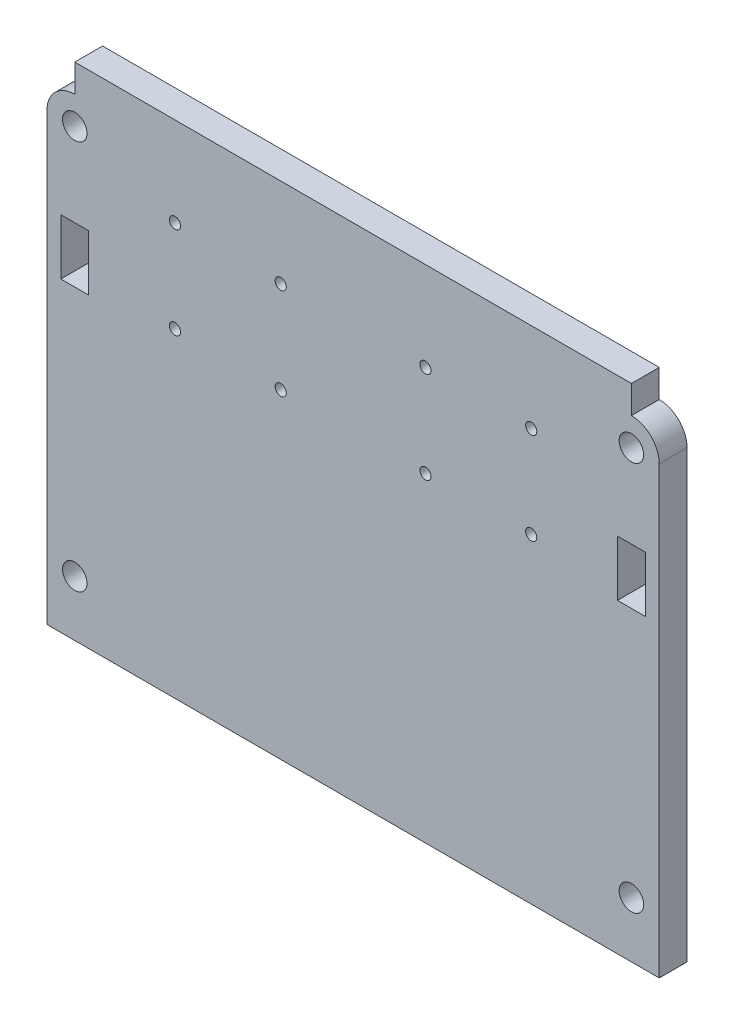
SolidWorks part; units mm, degrees
ref_plane "Front Plane" through (0, 0, 0) normal (0, 0, 1) x (1, 0, 0)
ref_plane "Top Plane" through (0, 0, 0) normal (0, 1, 0) x (1, 0, 0)
ref_plane "Right Plane" through (0, 0, 0) normal (1, 0, 0) x (0, 0, -1)
sketch "Sketch1" plane through (0, 0, 0) normal (0, 0, 1) x (1, 0, 0)
  line L0 (0, 105) -> (0, 110)
  line L1 (0, 0) -> (30.7314, 0) construction
  line L2 (0, 20) -> (0, 25) construction
  line L3 (0, 110) -> (100, 110)
  line L4 (50, 20) -> (50, 110) construction
  line L5 (0, 85) -> (2.5, 85)
  line L6 (0, 35) -> (0, 75) construction
  line L7 (0, 75) -> (2.5, 75)
  line L8 (2.5, 85) -> (2.5, 75)
  line L9 (0, 85) -> (0, 95) construction
  line L10 (0, 20) -> (100, 20)
  line L11 (0, 0) -> (0, 20) construction
  line L12 (-5, 100) -> (-5, 20)
  line L13 (0, 20) -> (-5, 20)
  line L14 (0, 85) -> (-2.5, 85)
  line L15 (-2.5, 85) -> (-2.5, 75)
  line L16 (-2.5, 75) -> (0, 75)
  line L17 (100, 85) -> (100, 95) construction
  line L18 (100, 35) -> (100, 75) construction
  line L19 (100, 20) -> (100, 25) construction
  line L20 (102.5, 75) -> (100, 75)
  line L21 (102.5, 85) -> (102.5, 75)
  line L22 (100, 85) -> (102.5, 85)
  line L23 (100, 20) -> (105, 20)
  line L24 (105, 100) -> (105, 20)
  line L25 (97.5, 85) -> (97.5, 75)
  line L26 (100, 75) -> (97.5, 75)
  line L27 (100, 85) -> (97.5, 85)
  line L28 (100, 105) -> (100, 110)
  arc A0 (0, 105) -> (0, 95) centre (0, 100) ccw construction
  circle A1 centre (0, 100) radius 2.2
  arc A2 (0, 35) -> (0, 25) centre (0, 30) ccw construction
  circle A3 centre (0, 30) radius 2.2
  arc A4 (0, 105) -> (-5, 100) centre (0, 100) ccw
  arc A5 (100, 35) -> (100, 25) centre (100, 30) cw construction
  arc A6 (100, 105) -> (100, 95) centre (100, 100) cw construction
  arc A7 (100, 105) -> (105, 100) centre (100, 100) cw
  circle A8 centre (100, 30) radius 2.2
  circle A9 centre (100, 100) radius 2.2
  dimension "D7" = 10
  dimension "D8" = 4.4
  dimension "D9" = 10
  dimension "D11" = 4.4
  dimension "D1" = 110
  dimension "D2" = 50
  dimension "D3" = 25
  dimension "D4" = 10
  dimension "D5" = 2.5
  dimension "D6" = 10
  dimension "D10" = 70
  dimension "D12" = 10
  dimension "D13" = 5
extrude "Boss-Extrude1" add sketch "Sketch1" along normal blind 5
sketch "Sketch2" plane through (0, 0, 5) normal (0, 0, 1) x (1, 0, 0)
  line L0 (-5, 70) -> (105, 70) construction
  line L1 (-5, 100) -> (-5, 20) construction
  line L2 (105, 20) -> (105, 100) construction
  line L3 (100, 110) -> (0, 110) construction
  line L4 (10, 77.5) -> (45, 77.5) construction
  line L5 (10, 70) -> (45, 70) construction
  line L6 (10, 70) -> (10, 94) construction
  line L7 (10, 94) -> (45, 94) construction
  line L8 (45, 70) -> (45, 94) construction
  line L9 (18, 94) -> (18, 70) construction
  line L10 (37, 94) -> (37, 70) construction
  line L11 (50, 110) -> (50, 20) construction
  line L12 (-5, 20) -> (105, 20) construction
  circle A0 centre (18, 94) radius 1
  circle A1 centre (37, 94) radius 1
  circle A2 centre (18, 77.5) radius 1
  circle A3 centre (37, 77.5) radius 1
  circle A4 centre (63, 77.5) radius 1
  circle A5 centre (82, 77.5) radius 1
  circle A6 centre (63, 94) radius 1
  circle A7 centre (82, 94) radius 1
  dimension "D8" = 2
  dimension "D9" = 2
  dimension "D10" = 2
  dimension "D11" = 2
  dimension "D1" = 40
  dimension "D2" = 35
  dimension "D3" = 24
  dimension "D4" = 7.5
  dimension "D5" = 8
  dimension "D6" = 8
  dimension "D7" = 5
extrude "Cut-Extrude1" cut sketch "Sketch2" against normal through all
